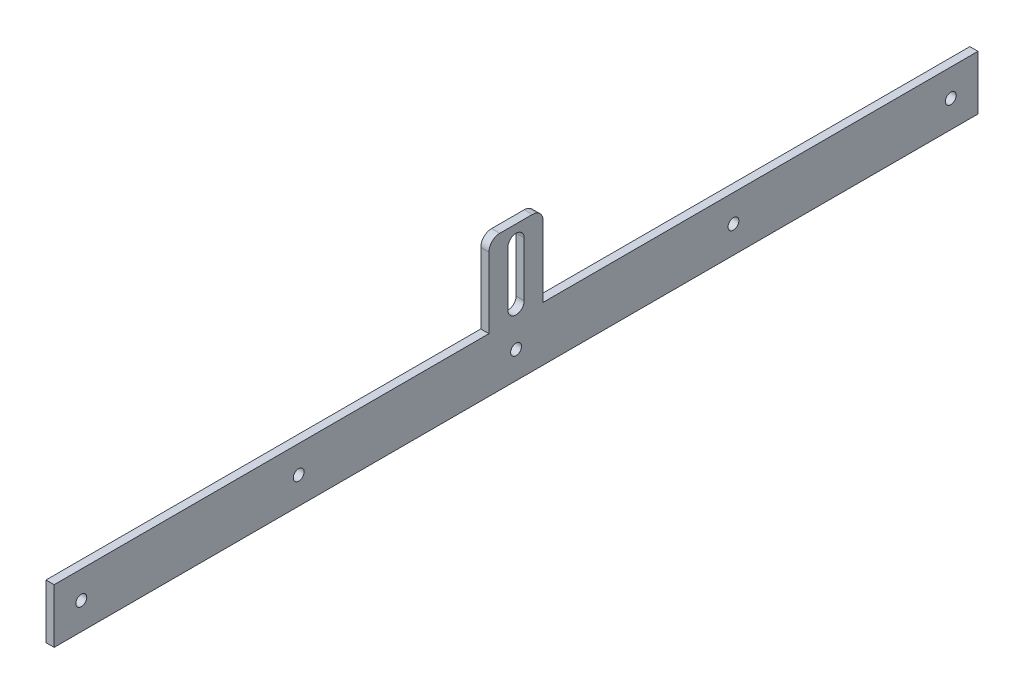
SolidWorks part; units mm, degrees
ref_plane "Ön Düzlem" through (0, 0, 0) normal (0, 0, 1) x (1, 0, 0)
ref_plane "Üst Düzlem" through (0, 0, 0) normal (0, 1, 0) x (1, 0, 0)
ref_plane "Sağ Düzlem" through (0, 0, 0) normal (1, 0, 0) x (0, 0, -1)
sketch "Sketch1" plane through (0, 0, 0) normal (1, 0, 0) x (0, 0, -1)
  line L1 (0, 0) -> (340, 0)
  line L2 (0, 0) -> (0, 20)
  line L3 (0, 20) -> (340, 20)
  line L4 (340, 0) -> (340, 20)
  dimension "D1" = 340
  dimension "D2" = 20
extrude "Boss-Extrude1" add sketch "Sketch1" along normal blind 3
sketch "Sketch2" plane through (3, 0, 0) normal (1, 0, 0) x (0, 0, -1)
  line L0 (0, 10) -> (340, 10) construction
  line L1 (0, 20) -> (0, 0) construction
  line L2 (340, 0) -> (340, 20) construction
  circle A0 centre (10, 10) radius 2
  circle A1 centre (90, 10) radius 2
  circle A2 centre (170, 10) radius 2
  circle A3 centre (250, 10) radius 2
  circle A4 centre (330, 10) radius 2
  dimension "D1" = 4
  dimension "D4" = 80
  dimension "D2" = 10
  dimension "D3" = 5
extrude "Cut-Extrude1" cut sketch "Sketch2" against normal blind 10
sketch "Sketch3" plane through (3, 0, 0) normal (1, 0, 0) x (0, 0, -1)
  line L0 (170, 20) -> (170, 103.1612) construction
  line L1 (340, 20) -> (0, 20) construction
  line L2 (170, 44) -> (170, 24) construction
  line L4 (160, 20) -> (160, 46)
  line L5 (164, 50) -> (176, 50)
  line L6 (180, 20) -> (180, 46)
  line L7 (173, 44) -> (173, 24)
  line L8 (167, 44) -> (167, 24)
  arc A0 (173, 44) -> (167, 44) centre (170, 44) ccw
  arc A1 (167, 24) -> (173, 24) centre (170, 24) ccw
  arc A2 (160, 46) -> (164, 50) centre (164, 46) cw
  arc A3 (180, 46) -> (176, 50) centre (176, 46) ccw
  point P10 (170, 34)
  point P17 (160, 50)
  point P20 (180, 50)
  line M9 (340, 20) -> (0, 20)
  dimension "D6" = 4
  dimension "D1" = 30
  dimension "D2" = 20
  dimension "D3" = 20
  dimension "D4" = 6
  dimension "D5" = 4
extrude "Boss-Extrude4" add sketch "Sketch3" against normal blind 3 contours L6 A3 L5 A2 L4 A1 L8 A0 L7 M9
